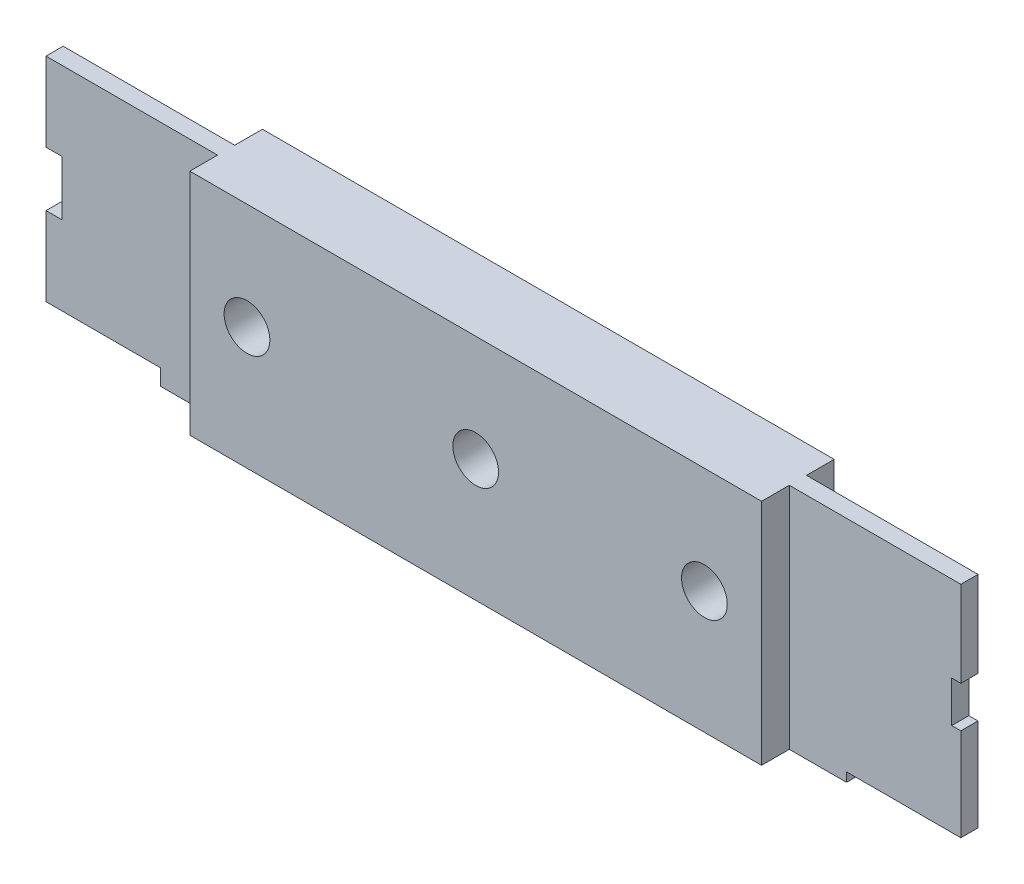
SolidWorks part; units mm, degrees
ref_plane "Alzado" through (0, 0, 0) normal (0, 0, 1) x (1, 0, 0)
ref_plane "Planta" through (0, 0, 0) normal (0, 1, 0) x (1, 0, 0)
ref_plane "Vista lateral" through (0, 0, 0) normal (1, 0, 0) x (0, 0, -1)
sketch "Croquis1" plane through (0, 0, 0) normal (0, 0, 1) x (1, 0, 0)
  line L0 (-40, 9.3) -> (40, 9.3)
  line L1 (40, 9.3) -> (40, 1.8)
  line L2 (40, 1.8) -> (39.2, 1.8)
  line L3 (39.2, 1.8) -> (39.2, -1.8)
  line L4 (39.2, -1.8) -> (40, -1.8)
  line L5 (40, -1.8) -> (40, -9.9)
  line L6 (40, -9.9) -> (30, -9.9)
  line L7 (30, -9.9) -> (30, -10.7)
  line L8 (30, -10.7) -> (-30, -10.7)
  line L9 (-30, -10.7) -> (-30, -9.3)
  line L10 (-30, -9.3) -> (-40, -9.3)
  line L11 (-40, -9.3) -> (-40, -2.4)
  line L12 (-40, -2.4) -> (-38.6, -2.4)
  line L13 (-38.6, -2.4) -> (-38.6, 2.4)
  line L14 (-38.6, 2.4) -> (-40, 2.4)
  line L15 (-40, 2.4) -> (-40, 9.3)
  line L16 (39.2, 0) -> (-38.6, 0) construction
  circle A0 centre (20, 0) radius 2
  circle A1 centre (0, 0) radius 2
  circle A2 centre (-20, 0) radius 2
  point P16 (-38.6, 0)
  point P18 (39.2, 0)
  point P19 (0, 9.3)
  dimension "D9" = 4
  dimension "D10" = 20
  dimension "D11" = 20
  dimension "D12" = 20
  dimension "D1" = 80
  dimension "D2" = 10
  dimension "D3" = 10
  dimension "D4" = 20
  dimension "D5" = 4.8
  dimension "D6" = 3.6
  dimension "D7" = 1.4
  dimension "D8" = 0.8
extrude "Saliente-Extruir1" add sketch "Croquis1" along normal mid plane 1.5
sketch "Croquis2" plane through (0, 0, 0) normal (0, 0, 1) x (1, 0, 0)
  line L0 (40, 9.3) -> (-40, 9.3) construction
  line L1 (-25, 9.3) -> (25, 9.3)
  line L2 (-25, 9.3) -> (-25, -10.7)
  line L3 (-25, -10.7) -> (25, -10.7)
  line L4 (25, 9.3) -> (25, -10.7)
  line L5 (-30, -10.7) -> (30, -10.7) construction
  line L6 (-40, 9.3) -> (-40, 2.4) construction
  line L7 (40, 1.8) -> (40, 9.3) construction
  circle A0 centre (-20, 0) radius 2
  circle A1 centre (0, 0) radius 2
  circle A2 centre (20, 0) radius 2
  dimension "D1" = 15
  dimension "D2" = 15
extrude "Saliente-Extruir2" add sketch "Croquis2" along normal mid plane 6.35
